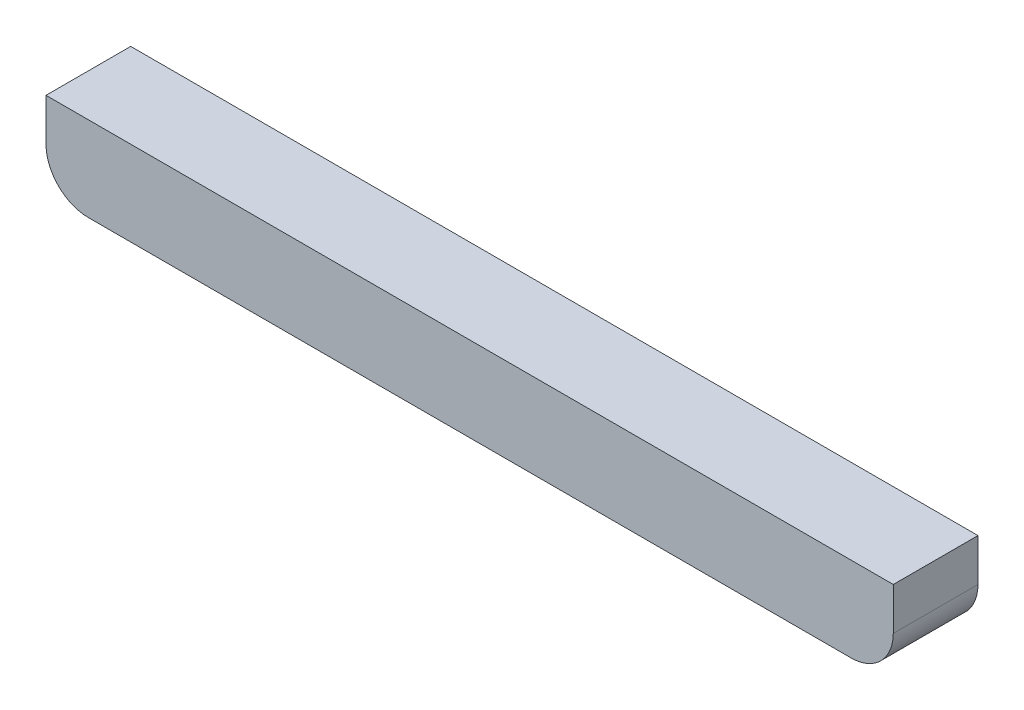
SolidWorks part; units mm, degrees
ref_plane "Front Plane" through (0, 0, 0) normal (0, 0, 1) x (1, 0, 0)
ref_plane "Top Plane" through (0, 0, 0) normal (0, 1, 0) x (1, 0, 0)
ref_plane "Right Plane" through (0, 0, 0) normal (1, 0, 0) x (0, 0, -1)
sketch "Sketch1" plane through (0, 0, 0) normal (0, 0, 1) x (1, 0, 0)
  line L1 (0, 0) -> (50.8, 0)
  line L2 (0, 0) -> (0, 5.08)
  line L3 (0, 5.08) -> (50.8, 5.08)
  line L4 (50.8, 0) -> (50.8, 5.08)
  dimension "D1" = 5.08
  dimension "D2" = 50.8
extrude "Boss-Extrude1" add sketch "Sketch1" along normal blind 5.08
fillet "Fillet1" radius 2.54 2 edges at (0, 0, 2.54) (50.8, 0, 2.54)
